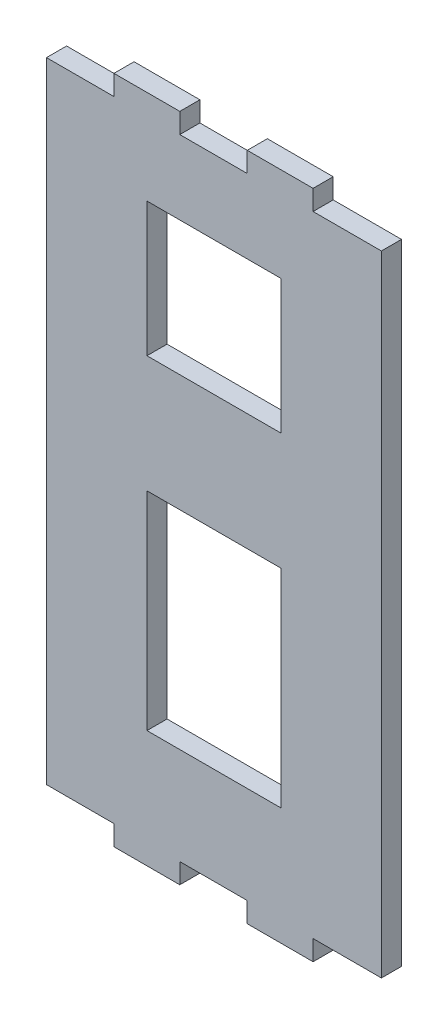
SolidWorks part; units mm, degrees
ref_plane "Plan de face" through (0, 0, 0) normal (0, 0, 1) x (1, 0, 0)
ref_plane "Plan de dessus" through (0, 0, 0) normal (0, 1, 0) x (1, 0, 0)
ref_plane "Plan de droite" through (0, 0, 0) normal (1, 0, 0) x (0, 0, -1)
sketch "Esquisse1" plane through (0, 0, 0) normal (0, 0, 1) x (1, 0, 0)
  line L1 (0, 0) -> (50, 0)
  line L2 (0, 0) -> (0, 100)
  line L3 (0, 100) -> (50, 100)
  line L4 (50, 0) -> (50, 100)
  dimension "D1" = 50
  dimension "D2" = 100
extrude "Boss.-Extru.1" add sketch "Esquisse1" along normal blind 3
sketch "Esquisse3" plane through (0, 0, 3) normal (0, 0, 1) x (1, 0, 0)
  line L0 (0, 100) -> (0, 0) construction
  line L1 (15, 85.9537) -> (35, 85.9537)
  line L2 (15, 85.9537) -> (15, 65.9537)
  line L3 (15, 65.9537) -> (35, 65.9537)
  line L4 (35, 85.9537) -> (35, 65.9537)
  line L6 (35, 17.4897) -> (15, 17.4897)
  line L7 (35, 17.4897) -> (35, 48.4897)
  line L8 (35, 48.4897) -> (15, 48.4897)
  line L9 (15, 17.4897) -> (15, 48.4897)
  dimension "D1" = 20
  dimension "D2" = 20
  dimension "D3" = 15
  dimension "D4" = 31
  dimension "D5" = 20
  dimension "D6" = 15
extrude "Enlèv. mat.-Extru.2" cut sketch "Esquisse3" against normal blind 3
sketch "Esquisse5" plane through (0, 0, 3) normal (0, 0, 1) x (1, 0, 0)
  line L0 (19.9, 100) -> (29.97, 100)
  line L1 (0, 100) -> (10.07, 100)
  line L2 (0, 100) -> (0, 97)
  line L3 (0, 97) -> (10.07, 97)
  line L4 (10.07, 100) -> (10.07, 97)
  line L5 (19.9, 100) -> (19.9, 97)
  line L6 (19.9, 97) -> (29.97, 97)
  line L7 (29.97, 100) -> (29.97, 97)
  line L8 (39.8, 100) -> (49.87, 100)
  line L9 (39.8, 100) -> (39.8, 97)
  line L10 (39.8, 97) -> (49.87, 97)
  line L11 (49.87, 100) -> (49.87, 97)
  line L12 (19.9, 3) -> (29.97, 3)
  line L13 (19.9, 3) -> (19.9, 0)
  line L14 (19.9, 0) -> (29.97, 0)
  line L15 (29.97, 3) -> (29.97, 0)
  line L16 (39.8, 3) -> (49.87, 3)
  line L17 (39.8, 3) -> (39.8, 0)
  line L18 (39.8, 0) -> (49.87, 0)
  line L19 (49.87, 3) -> (49.87, 0)
  line L20 (0, 3) -> (10.07, 3)
  line L21 (0, 3) -> (0, 0)
  line L22 (0, 0) -> (10.07, 0)
  line L23 (10.07, 3) -> (10.07, 0)
  dimension "D1" = 10.07
  dimension "D2" = 3
  dimension "D3" = 2
extrude "Enlèv. mat.-Extru.3" cut sketch "Esquisse5" against normal blind 3
sketch "Esquisse6" plane through (0, 0, 3) normal (0, 0, 1) x (1, 0, 0)
  line L0 (50, 0) -> (50, 100) construction
  line L1 (49.87, 100) -> (50, 100)
  line L2 (49.87, 100) -> (49.87, 97)
  line L3 (49.87, 97) -> (50, 97)
  line L4 (50, 100) -> (50, 97)
  line L5 (49.87, 3) -> (49.87, 0)
  line L6 (49.87, 3) -> (50, 3)
  line L7 (50, 3) -> (50, 0)
  line L8 (49.87, 0) -> (50, 0)
  dimension "D2" = 3
  dimension "D1" = 2
extrude "Enlèv. mat.-Extru.4" cut sketch "Esquisse6" against normal blind 3
